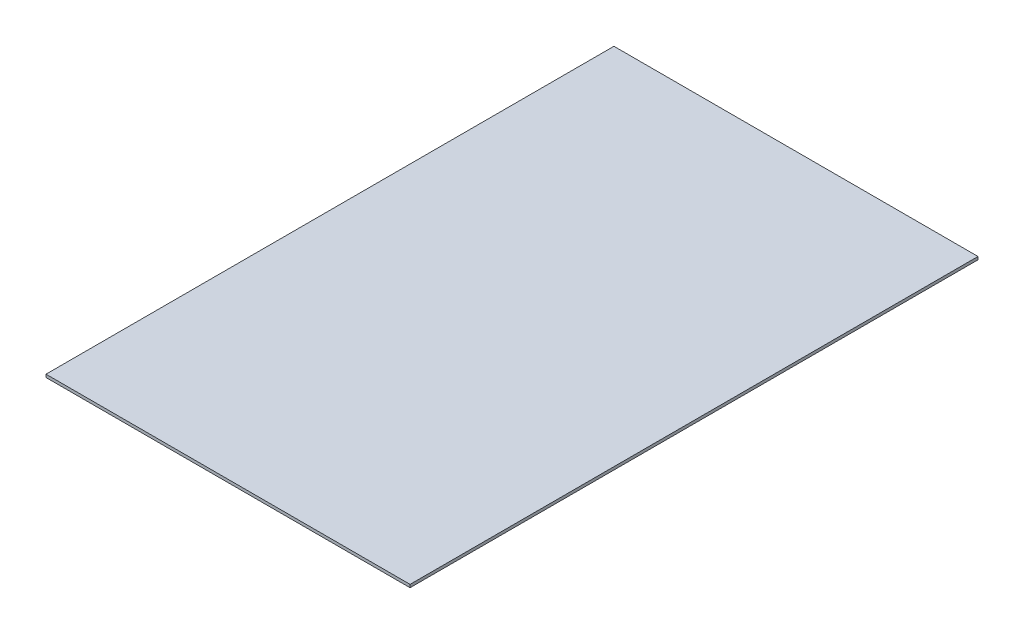
SolidWorks part; units mm, degrees
ref_plane "Front Plane" through (0, 0, 0) normal (0, 0, 1) x (1, 0, 0)
ref_plane "Top Plane" through (0, 0, 0) normal (0, 1, 0) x (1, 0, 0)
ref_plane "Right Plane" through (0, 0, 0) normal (1, 0, 0) x (0, 0, -1)
sketch "Sketch1" plane through (0, 0, 0) normal (0, 1, 0) x (1, 0, 0)
  line L1 (-158.75, -247.65) -> (158.75, -247.65)
  line L2 (-158.75, -247.65) -> (-158.75, 247.65)
  line L3 (-158.75, 247.65) -> (158.75, 247.65)
  line L4 (158.75, -247.65) -> (158.75, 247.65)
  line L5 (-158.75, -247.65) -> (158.75, 247.65) construction
  line L6 (-158.75, 247.65) -> (158.75, -247.65) construction
  point P0 (0, 0)
  dimension "D1" = 495.3
  dimension "D2" = 317.5
extrude "Boss-Extrude1" add sketch "Sketch1" along normal blind 2.54
